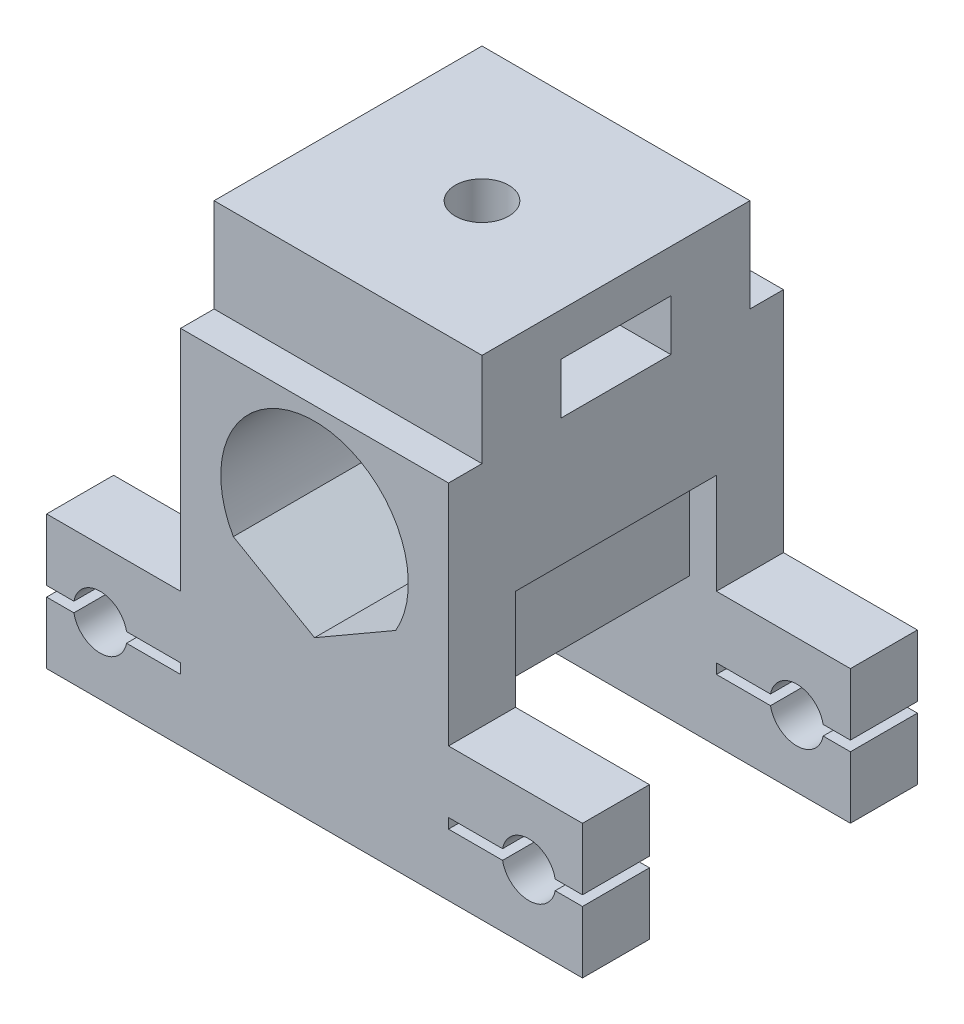
SolidWorks part; units mm, degrees
ref_plane "Front Plane" through (0, 0, 0) normal (0, 0, 1) x (1, 0, 0)
ref_plane "Top Plane" through (0, 0, 0) normal (0, 1, 0) x (1, 0, 0)
ref_plane "Right Plane" through (0, 0, 0) normal (1, 0, 0) x (0, 0, -1)
sketch "Sketch1" plane through (0, 0, 0) normal (0, 1, 0) x (1, 0, 0)
  line L1 (-10, -12.5) -> (10, -12.5)
  line L2 (-10, -12.5) -> (-10, 12.5)
  line L3 (-10, 12.5) -> (10, 12.5)
  line L4 (10, -12.5) -> (10, 12.5)
  line L5 (-10, -12.5) -> (10, 12.5) construction
  line L6 (-10, 12.5) -> (10, -12.5) construction
  point P0 (0, 0)
  dimension "D1" = 20
  dimension "D2" = 25
extrude "Boss-Extrude1" add sketch "Sketch1" along normal blind 17
sketch "Sketch2" plane through (0, 0, 12.5) normal (0, 0, 1) x (1, 0, 0)
  line L0 (0, 2) -> (-6.0622, 5.5)
  line L1 (-10, 0) -> (10, 0) construction
  line L2 (0, 2) -> (-6.4072, 2) construction
  line L3 (0, 17) -> (0, 16) construction
  line L4 (0, -55) -> (0, 55) construction
  line L5 (-10, 17) -> (10, 17) construction
  line L7 (0, 9) -> (0, 2) construction
  line L8 (0, 2) -> (6.0622, 5.5)
  arc A0 (6.0622, 5.5) -> (-6.0622, 5.5) centre (0, 9) ccw
  dimension "D1" = 2
  dimension "D2" = 3.5
  dimension "D3" = 30
extrude "Cut-Extrude1" cut sketch "Sketch2" against normal through all
ref_plane "Plane1" through (0, 0, 1.5) normal (0, 0, 1) x (1, 0, 0)
sketch "Sketch3" plane through (0, 0, 12.5) normal (0, 0, 1) x (1, 0, 0)
  line L0 (10, 0) -> (20, 0)
  line L1 (20, 0) -> (20, -10)
  line L2 (20, -10) -> (-20, -10)
  line L3 (-20, -10) -> (-20, 0)
  line L4 (-20, 0) -> (-10, 0)
  line L5 (-10, 0) -> (10, 0)
  dimension "D1" = 10
  dimension "D2" = 10
  dimension "D3" = 10
extrude "Boss-Extrude2" add sketch "Sketch3" against normal blind 5
mirror "Mirror1" about plane through (0, 0, 0) normal (0, 0, 1) of "Boss-Extrude2"
sketch "Sketch4" plane through (0, 0, 12.5) normal (0, 0, 1) x (1, 0, 0)
  line L0 (20, -10) -> (20, 0) construction
  line L1 (20, 0) -> (10, 0) construction
  line L2 (0, -13.75) -> (0, 13.75) construction
  circle A0 centre (16, -5) radius 2
  circle A1 centre (-16, -5) radius 2
  dimension "D1" = 4
  dimension "D2" = 4
  dimension "D3" = 5
extrude "Cut-Extrude2" cut sketch "Sketch4" against normal through all
sketch "Sketch6" plane through (0, 17, 0) normal (0, 1, 0) x (1, 0, 0)
  line L0 (10, -12.5) -> (10, 12.5) construction
  line L1 (-10, -10) -> (10, -10)
  line L2 (-10, -10) -> (-10, 10)
  line L3 (-10, 10) -> (10, 10)
  line L4 (10, -10) -> (10, 10)
  line L5 (-10, -10) -> (10, 10) construction
  line L6 (-10, 10) -> (10, -10) construction
  point P0 (0, 0)
  dimension "D1" = 20
extrude "Boss-Extrude3" add sketch "Sketch6" along normal blind 7 contours L2 L1 L4 L3
sketch "Sketch8" plane through (10, 0, 0) normal (1, 0, 0) x (0, 0, -1)
  line L0 (10, 17) -> (12.5, 17) construction
  line L5 (-4.1, 17) -> (4.1, 17)
  line L6 (-4.1, 17) -> (-4.1, 20.8)
  line L7 (-4.1, 20.8) -> (4.1, 20.8)
  line L8 (4.1, 17) -> (4.1, 20.8)
  line L9 (-4.1, 17) -> (4.1, 20.8) construction
  line L10 (-4.1, 20.8) -> (4.1, 17) construction
  line L11 (-10, 24) -> (-10, 17) construction
  point P0 (0, 18.9)
  point P7 (0, 0)
  point P8 (0, 18.95)
  dimension "D1" = 8.2
  dimension "D2" = 3.8
  dimension "D3" = 5.9
extrude "Cut-Extrude3" cut sketch "Sketch8" against normal through all
sketch "Sketch7" plane through (0, 24, 0) normal (0, 1, 0) x (1, 0, 0)
  circle A0 centre (0, 0) radius 2
extrude "Cut-Extrude4" cut sketch "Sketch7" against normal up to surface (8 mm away)
sketch "Sketch9" plane through (10, 0, 0) normal (-1, 0, 0) x (0, 0, 1)
  line L0 (-12.5, 0) -> (-7.5, 0) construction
  line L1 (-7.5, 0) -> (7.5, 0)
  line L2 (-7.5, 0) -> (-7.5, 7.5)
  line L3 (-7.5, 7.5) -> (7.5, 7.5)
  line L4 (7.5, 0) -> (7.5, 7.5)
  point P6 (0, 0)
  dimension "D1" = 7.5
extrude "Cut-Extrude5" cut sketch "Sketch9" along normal blind 2
sketch "Sketch10" plane through (0, 0, 12.5) normal (0, 0, 1) x (1, 0, 0)
  line L0 (-20, 0) -> (-20, -10) construction
  line L1 (-20, -4.625) -> (-10, -4.625)
  line L2 (-20, -4.625) -> (-20, -5.375)
  line L3 (-20, -5.375) -> (-10, -5.375)
  line L4 (-10, -4.625) -> (-10, -5.375)
  line L5 (0, -0.8665) -> (0, -10) construction
  line L6 (-20, -10) -> (20, -10) construction
  line L7 (20, -4.625) -> (20, -5.375)
  line L8 (10, -4.625) -> (10, -5.375)
  line L9 (20, -5.375) -> (10, -5.375)
  line L10 (20, -4.625) -> (10, -4.625)
  circle A0 centre (-16, -5) radius 2 construction
  dimension "D1" = 0.75
  dimension "D2" = 0.375
  dimension "D3" = 10
extrude "Cut-Extrude6" cut sketch "Sketch10" against normal through all
